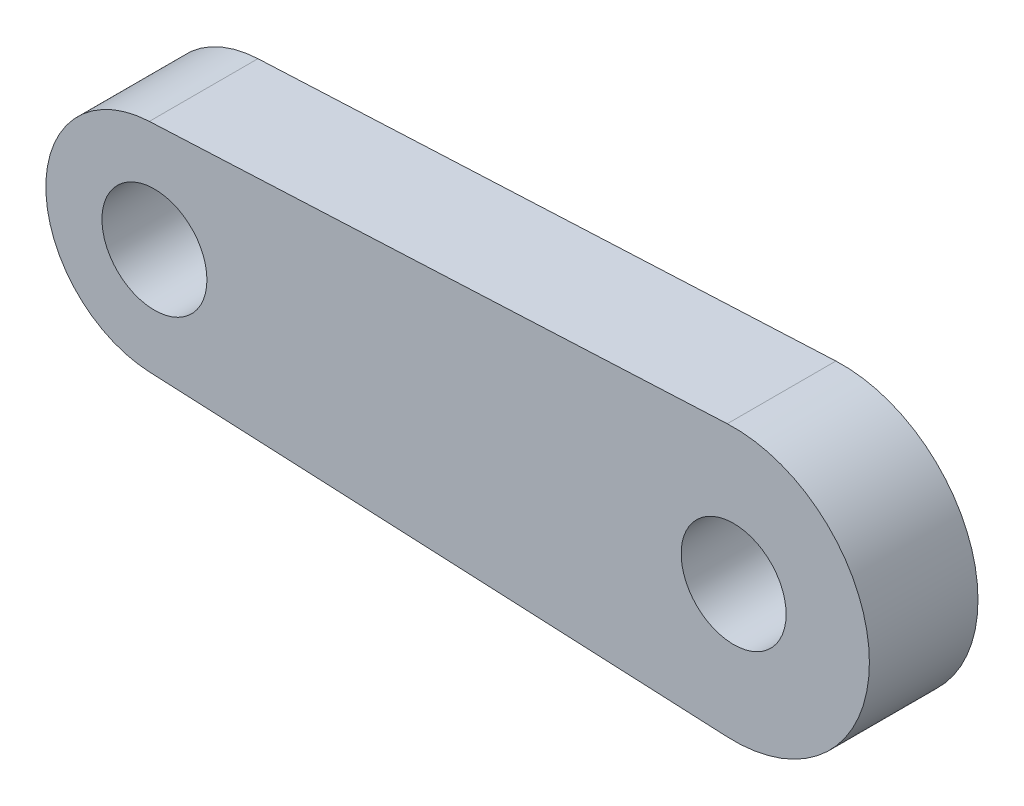
SolidWorks part; units mm, degrees
ref_plane "Plan de face" through (0, 0, 0) normal (0, 0, 1) x (1, 0, 0)
ref_plane "Plan de dessus" through (0, 0, 0) normal (0, 1, 0) x (1, 0, 0)
ref_plane "Plan de droite" through (0, 0, 0) normal (1, 0, 0) x (0, 0, -1)
sketch "Esquisse2" plane through (0, 0, 0) normal (0, 0, 1) x (1, 0, 0)
  line L0 (-8.5158, -2.9967) -> (7.4491, -3.7459)
  line L1 (7.4491, 3.7459) -> (-8.5158, 2.9967)
  arc A0 (7.4491, -3.7459) -> (7.4491, 3.7459) centre (7.6248, 0) ccw
  arc A3 (-8.5158, 2.9967) -> (-8.5158, -2.9967) centre (-8.3752, 0) ccw
  circle A4 centre (7.6248, 0) radius 1.45
  circle A5 centre (-8.3752, 0) radius 1.45
  dimension "D2" = 2.9
  dimension "D3" = 2.9
  dimension "D4" = 3.75
  dimension "D5" = 3
  dimension "D1" = 16
extrude "Boss.-Extru.1" add sketch "Esquisse2" along normal blind 3
